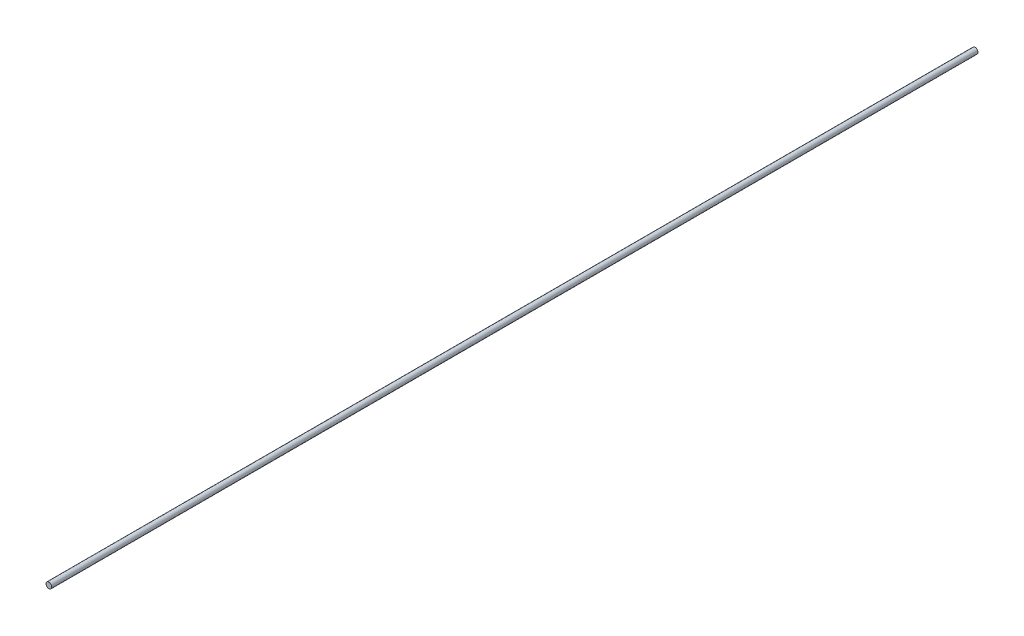
SolidWorks part; units mm, degrees
ref_plane "前视基准面" through (0, 0, 0) normal (0, 0, 1) x (1, 0, 0)
ref_plane "上视基准面" through (0, 0, 0) normal (0, 1, 0) x (1, 0, 0)
ref_plane "右视基准面" through (0, 0, 0) normal (1, 0, 0) x (0, 0, -1)
other "Configuration Table"
sketch "草图1" plane through (0, 0, 0) normal (0, 0, 1) x (1, 0, 0)
  circle A0 centre (0, 0) radius 0.4
extrude "D0p8钢索跨度_L128.6976" add sketch "草图1" along normal blind 128.6976
